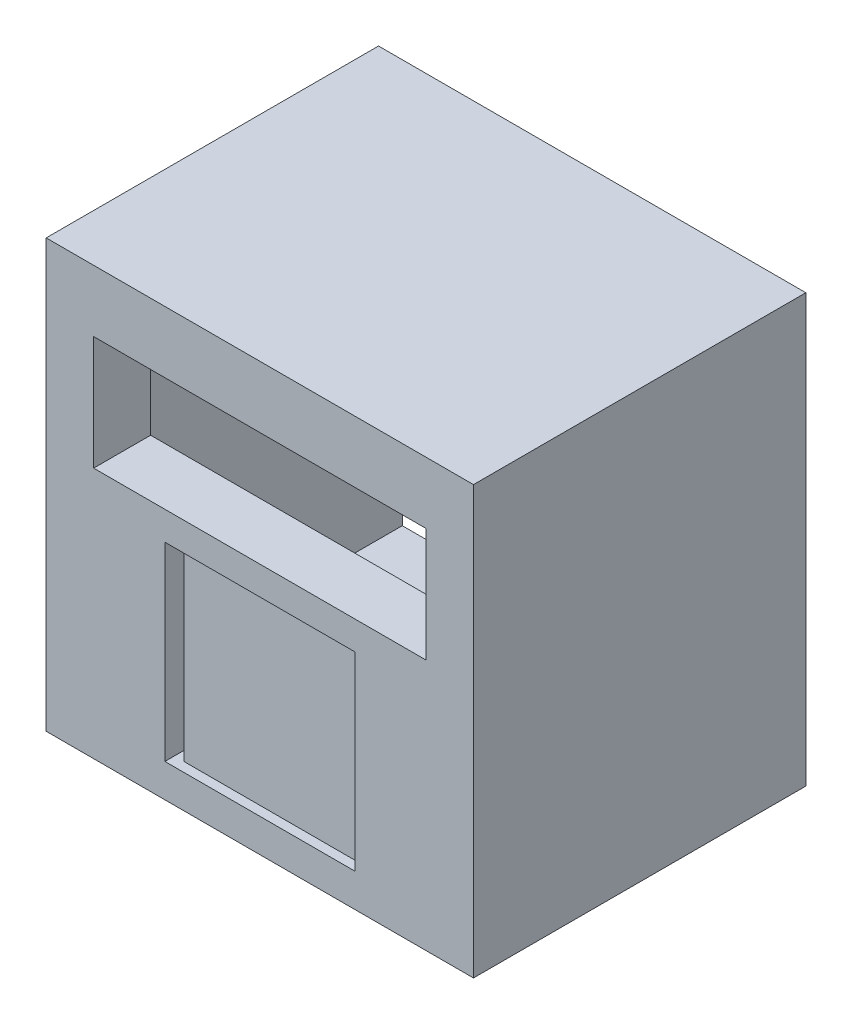
SolidWorks part; units mm, degrees
ref_plane "Front Plane" through (0, 0, 0) normal (0, 0, 1) x (1, 0, 0)
ref_plane "Top Plane" through (0, 0, 0) normal (0, 1, 0) x (1, 0, 0)
ref_plane "Right Plane" through (0, 0, 0) normal (1, 0, 0) x (0, 0, -1)
sketch "Sketch1" plane through (0, 0, 0) normal (0, 0, 1) x (1, 0, 0)
  line L1 (-45, -45) -> (45, -45)
  line L2 (-45, -45) -> (-45, 45)
  line L3 (-45, 45) -> (45, 45)
  line L4 (45, -45) -> (45, 45)
  line L5 (-45, -45) -> (45, 45) construction
  line L6 (-45, 45) -> (45, -45) construction
  point P0 (0, 0)
  dimension "D1" = 90
  dimension "D2" = 90
extrude "Boss-Extrude1" add sketch "Sketch1" along normal blind 70
shell "Shell2" thickness 5
sketch "Sketch2" plane through (0, 0, 70) normal (0, 0, 1) x (1, 0, 0)
  line L0 (0, 45) -> (0, -45) construction
  line L1 (45, 45) -> (-45, 45) construction
  line L2 (-45, -45) -> (45, -45) construction
  line L4 (-35, 8) -> (35, 8)
  line L5 (-35, 8) -> (-35, 32)
  line L6 (-35, 32) -> (35, 32)
  line L7 (35, 8) -> (35, 32)
  line L8 (-35, 8) -> (35, 32) construction
  line L9 (-35, 32) -> (35, 8) construction
  point P6 (0, 20)
  point P12 (0, 20)
  dimension "D1" = 70
  dimension "D2" = 24
  dimension "D3" = 25
extrude "Cut-Extrude1" cut sketch "Sketch2" against normal up to next contours L4 L7 L6 L5
sketch "Sketch4" plane through (0, 0, 65) normal (0, 0, -1) x (-1, 0, 0)
  line L0 (-40, 32) -> (35, 32)
  line L1 (-40, 2) -> (40, 2)
  line L2 (-40, 2) -> (-40, 38)
  line L3 (-40, 38) -> (40, 38)
  line L4 (40, 2) -> (40, 38)
  line L5 (-40, 2) -> (40, 38) construction
  line L6 (-40, 38) -> (40, 2) construction
  line L7 (35, 32) -> (35, 8)
  line L8 (35, 8) -> (-40, 8)
  point P0 (0, 20)
  line M3 (35, 8) -> (-35, 8)
  line M5 (-35, 32) -> (35, 32)
  line M6 (35, 32) -> (35, 8)
  line M7 (-40, 40) -> (-40, -40)
  line M9 (40, -40) -> (40, 40)
  dimension "D1" = 80
  dimension "D2" = 36
extrude "Boss-Extrude2" add sketch "Sketch4" along normal blind 7 contours L8 L2 L1 L3 L0 M3 M9 M7 M5 M6
sketch "Sketch5" plane through (0, 0, 70) normal (0, 0, 1) x (1, 0, 0)
  line L1 (-20, -38) -> (20, -38)
  line L2 (-20, -38) -> (-20, 2)
  line L3 (-20, 2) -> (20, 2)
  line L4 (20, -38) -> (20, 2)
  line L5 (-20, -38) -> (20, 2) construction
  line L6 (-20, 2) -> (20, -38) construction
  line L8 (-35, 8) -> (35, 8) construction
  point P0 (0, -18)
  point P11 (0, 8)
  dimension "D1" = 40
  dimension "D2" = 40
  dimension "D3" = 26
extrude "Cut-Extrude2" cut sketch "Sketch5" against normal blind 2
sketch "Sketch6" plane through (0, 0, 68) normal (0, 0, 1) x (1, 0, 0)
  line L0 (-20, -38) -> (20, -38) construction
  line L1 (-18, -38) -> (-20, -38)
  line L2 (-18, -38) -> (-18, 2)
  line L3 (-18, 2) -> (-20, 2)
  line L4 (-20, -38) -> (-20, 2)
  line L5 (20, 2) -> (-20, 2) construction
  line L6 (20, 2) -> (-20, 2) construction
  line L7 (-20, 2) -> (-20, -38) construction
  dimension "D1" = 2
extrude "Cut-Extrude3" cut sketch "Sketch6" against normal up to next
